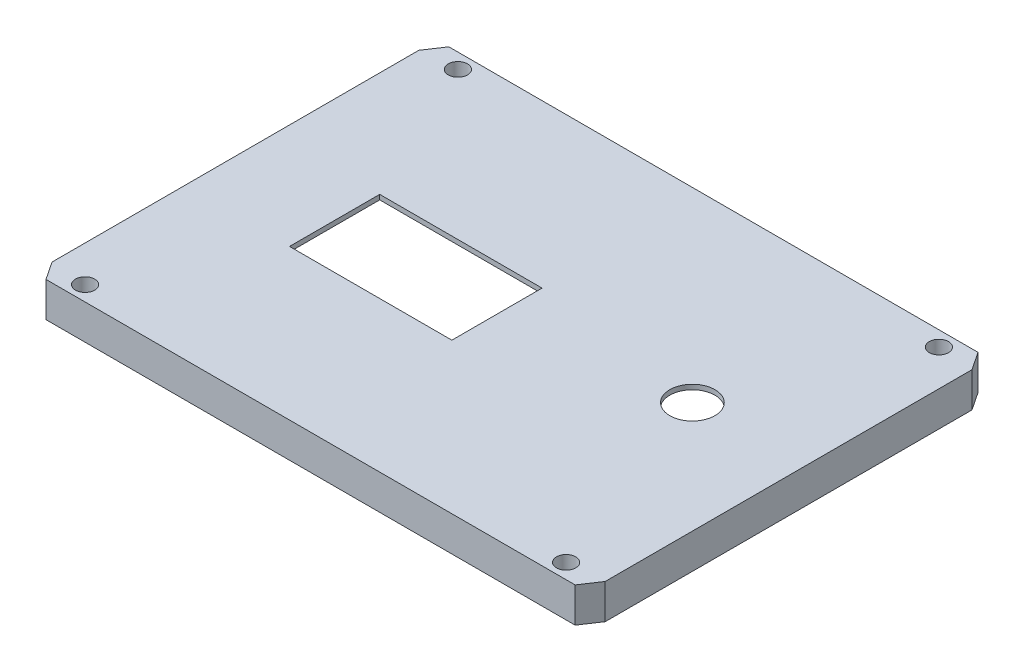
SolidWorks part; units mm, degrees
ref_plane "Front Plane" through (0, 0, 0) normal (0, 0, 1) x (1, 0, 0)
ref_plane "Top Plane" through (0, 0, 0) normal (0, 1, 0) x (1, 0, 0)
ref_plane "Right Plane" through (0, 0, 0) normal (1, 0, 0) x (0, 0, -1)
sketch "Sketch1" plane through (0, 0, 0) normal (0, 1, 0) x (1, 0, 0)
  line L1 (-44, 28.5) -> (44, 28.5)
  line L2 (-44, 28.5) -> (-44, -28.5)
  line L3 (-44, -28.5) -> (44, -28.5)
  line L4 (44, 28.5) -> (44, -28.5)
  line L5 (-44, 28.5) -> (44, -28.5) construction
  line L6 (-44, -28.5) -> (44, 28.5) construction
  line L7 (46, -33.5) -> (-46, -33.5)
  line L8 (46, -33.5) -> (46, 33.5)
  line L9 (46, 33.5) -> (-46, 33.5)
  line L10 (-46, -33.5) -> (-46, 33.5)
  line L11 (46, -33.5) -> (-46, 33.5) construction
  line L12 (46, 33.5) -> (-46, -33.5) construction
  point P0 (0, 0)
  point P6 (0, 0)
  dimension "D1" = 88
  dimension "D2" = 57
  dimension "D3" = 2
  dimension "D4" = 5
extrude "Boss-Extrude1" add sketch "Sketch1" along normal blind 25
sketch "Sketch2" plane through (0, 0, 0) normal (0, -1, 0) x (1, 0, 0)
  line L0 (-46, -33.5) -> (-46, 33.5) construction
  line L1 (46, -33.5) -> (-46, -33.5) construction
  line L2 (46, 33.5) -> (46, -33.5) construction
  line L3 (-46, 33.5) -> (46, 33.5) construction
  line L4 (-46, -33.5) -> (-46, 33.5)
  line L5 (46, -33.5) -> (-46, -33.5)
  line L6 (46, 33.5) -> (46, -33.5)
  line L7 (-46, 33.5) -> (46, 33.5)
extrude "Boss-Extrude2" add sketch "Sketch2" along normal blind 0.8
sketch "Sketch3" plane through (-46, 0, 0) normal (-1, 0, 0) x (0, 0, 1)
  line L0 (-28.5, 25) -> (-28.5, 0) construction
  line L1 (-5.5, 18.5) -> (5.5, 18.5)
  line L2 (-5.5, 18.5) -> (-5.5, 11.5)
  line L3 (-5.5, 11.5) -> (5.5, 11.5)
  line L4 (5.5, 18.5) -> (5.5, 11.5)
  line L5 (-5.5, 18.5) -> (5.5, 11.5) construction
  line L6 (-5.5, 11.5) -> (5.5, 18.5) construction
  line L8 (-28.5, 0) -> (28.5, 0) construction
  point P0 (0, 15)
  dimension "D1" = 11
  dimension "D2" = 7
  dimension "D3" = 23
  dimension "D4" = 15
extrude "Cut-Extrude1" cut sketch "Sketch3" against normal up to next
sketch "Sketch4" plane through (0, 25, 0) normal (0, 1, 0) x (1, 0, 0)
  line L0 (46, 33.5) -> (-46, 33.5) construction
  line L1 (40, -31) -> (-40, -31)
  line L2 (40, -31) -> (40, 31)
  line L3 (40, 31) -> (-40, 31)
  line L4 (-40, -31) -> (-40, 31)
  line L5 (40, -31) -> (-40, 31) construction
  line L6 (40, 31) -> (-40, -31) construction
  circle A0 centre (-40, 31) radius 1.6
  circle A1 centre (40, 31) radius 1.6
  circle A2 centre (40, -31) radius 1.6
  circle A3 centre (-40, -31) radius 1.6
  point P0 (0, 0)
  dimension "D3" = 3.2
  dimension "D1" = 2.5
  dimension "D2" = 80
extrude "Cut-Extrude2" cut sketch "Sketch4" against normal blind 8 contours L3 A0 L4 | L4 A0 L3 | L1 A3 L4 | L4 A3 L1 | L2 A2 L1 | L1 A2 L2 | L3 A1 L2 | L2 A1 L3
chamfer "Chamfer1" distance 3 distance2 2 2 edges at (46, 12.1, -33.5) (-46, 12.1, 33.5)
chamfer "Chamfer2" distance 2 distance2 3 2 edges at (-46, 12.1, -33.5) (46, 12.1, 33.5)
sketch "Sketch6" plane through (0, 25, 0) normal (0, 1, 0) x (1, 0, 0)
  line L9 (-28.5, 6.5) -> (-1.5, 6.5)
  line L10 (-28.5, 6.5) -> (-28.5, -8.5)
  line L11 (-28.5, -8.5) -> (-1.5, -8.5)
  line L12 (-1.5, 6.5) -> (-1.5, -8.5)
  line L13 (-28.5, 6.5) -> (-1.5, -8.5) construction
  line L14 (-28.5, -8.5) -> (-1.5, 6.5) construction
  line L17 (-44, 28.5) -> (-44, -28.5) construction
  line L18 (-44, -28.5) -> (44, -28.5) construction
  line L29 (44, 33.5) -> (-44, 33.5)
  line L30 (-44, 33.5) -> (-46, 30.5)
  line L31 (-46, 30.5) -> (-46, -30.5)
  line L32 (-46, -30.5) -> (-44, -33.5)
  line L33 (-44, -33.5) -> (44, -33.5)
  line L34 (44, -33.5) -> (46, -30.5)
  line L35 (46, -30.5) -> (46, 30.5)
  line L36 (46, 30.5) -> (44, 33.5)
  line L37 (44, 33.5) -> (-44, 33.5)
  line L38 (-44, 33.5) -> (-46, 30.5)
  line L39 (-46, 30.5) -> (-46, -30.5)
  line L40 (-46, -30.5) -> (-44, -33.5)
  line L41 (-44, -33.5) -> (44, -33.5)
  line L42 (44, -33.5) -> (46, -30.5)
  line L43 (46, -30.5) -> (46, 30.5)
  line L44 (46, 30.5) -> (44, 33.5)
  circle A0 centre (27.5, 2.5) radius 3.75
  point P6 (-15, -1)
  circle M13 centre (40, 31) radius 1.6
  circle M14 centre (40, -31) radius 1.6
  circle M15 centre (-40, -31) radius 1.6
  circle M16 centre (-40, 31) radius 1.6
  line M17 (-46, 30.5) -> (-46, -30.5)
  line M18 (-44, -33.5) -> (44, -33.5)
  line M19 (46, -30.5) -> (46, 30.5)
  line M20 (44, 33.5) -> (-44, 33.5)
  line M21 (-44, 28.5) -> (44, 28.5)
  line M22 (44, 28.5) -> (44, -28.5)
  line M23 (44, -28.5) -> (-44, -28.5)
  line M24 (-44, -28.5) -> (-44, 28.5)
  line M25 (-44, 33.5) -> (-46, 30.5)
  line M26 (-46, -30.5) -> (-44, -33.5)
  line M27 (44, -33.5) -> (46, -30.5)
  line M28 (46, 30.5) -> (44, 33.5)
  dimension "D5" = 7.5
  dimension "D1" = 15
  dimension "D2" = 27
  dimension "D3" = 15.5
  dimension "D4" = 20
  dimension "D6" = 71.5
  dimension "D7" = 31
  dimension "D8" = 0
extrude "Boss-Extrude3" add sketch "Sketch6" along normal blind 0.8 contours M28 M20 M25 M17 M26 M18 M27 M19 M14 M16 M24 M21 M22 M23 M15 M13 | A0 L9 L12 L11 L10 M21 M24 M23 M22
sketch "Sketch7" plane through (0, -0.8, 0) normal (0, -1, 0) x (1, 0, 0)
  line L8 (-46, 30.5) -> (-46, -30.5)
  line L9 (-46, -30.5) -> (-44, -33.5)
  line L10 (-44, -33.5) -> (44, -33.5)
  line L11 (44, -33.5) -> (46, -30.5)
  line L12 (46, -30.5) -> (46, 30.5)
  line L13 (46, 30.5) -> (44, 33.5)
  line L14 (44, 33.5) -> (-44, 33.5)
  line L15 (-44, 33.5) -> (-46, 30.5)
  line L16 (-46, 30.5) -> (-46, -30.5)
  line L17 (-46, -30.5) -> (-44, -33.5)
  line L18 (-44, -33.5) -> (44, -33.5)
  line L19 (44, -33.5) -> (46, -30.5)
  line L20 (46, -30.5) -> (46, 30.5)
  line L21 (46, 30.5) -> (44, 33.5)
  line L22 (44, 33.5) -> (-44, 33.5)
  line L23 (-44, 33.5) -> (-46, 30.5)
  dimension "D1" = 0
extrude "Cut-Extrude3" cut sketch "Sketch7" against normal blind 20.8
